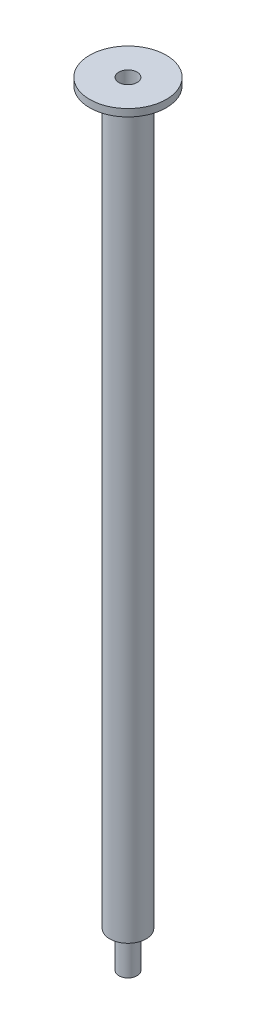
SolidWorks part; units mm, degrees
ref_plane "Front Plane" through (0, 0, 0) normal (0, 0, 1) x (1, 0, 0)
ref_plane "Top Plane" through (0, 0, 0) normal (0, 1, 0) x (1, 0, 0)
ref_plane "Right Plane" through (0, 0, 0) normal (1, 0, 0) x (0, 0, -1)
sketch "Sketch2" plane through (0, 0, 0) normal (0, 1, 0) x (1, 0, 0)
  circle A0 centre (0, 0) radius 5
  dimension "D1" = 10
extrude "Boss-Extrude1" add sketch "Sketch2" along normal blind 200
sketch "Sketch3" plane through (0, 200, 0) normal (0, 1, 0) x (1, 0, 0)
  circle A0 centre (0, 0) radius 10.5
  dimension "D1" = 21
extrude "Boss-Extrude2" add sketch "Sketch3" along normal blind 2
sketch "Sketch4" plane through (0, 202, 0) normal (0, 1, 0) x (1, 0, 0)
  circle A0 centre (0, 0) radius 2.5
  dimension "D1" = 5
extrude "Cut-Extrude1" cut sketch "Sketch4" against normal blind 10
sketch "Sketch5" plane through (0, 0, 0) normal (0, -1, 0) x (1, 0, 0)
  circle A0 centre (0, 0) radius 2.5
  dimension "D1" = 5
extrude "Boss-Extrude3" add sketch "Sketch5" along normal blind 10
